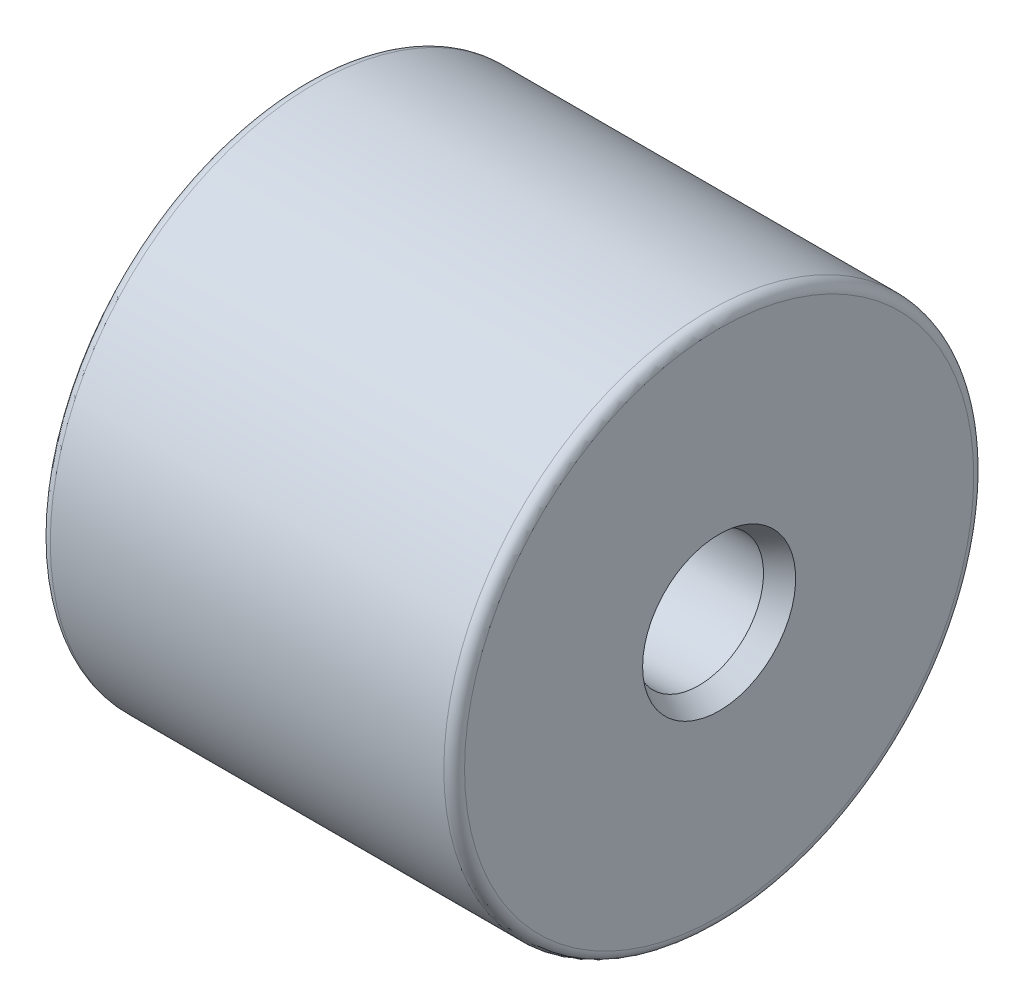
SolidWorks part; units mm, degrees
ref_plane "Front Plane" through (0, 0, 0) normal (0, 0, 1) x (1, 0, 0)
ref_plane "Top Plane" through (0, 0, 0) normal (0, 1, 0) x (1, 0, 0)
ref_plane "Right Plane" through (0, 0, 0) normal (1, 0, 0) x (0, 0, -1)
sketch "Sketch1" plane through (0, 0, 0) normal (0, 0, 1) x (1, 0, 0)
  line L0 (-1000, 0) -> (49000, 0) construction
  line L1 (-15.24, 19.4945) -> (15.24, 19.4945)
  line L2 (15.24, 19.4945) -> (15.24, 4.765)
  line L3 (15.24, 4.765) -> (-15.24, 4.765)
  line L4 (-15.24, 4.765) -> (-15.24, 19.4945)
  line L5 (0, -55) -> (0, 55) construction
  point P5 (0, 19.4945)
  dimension "D1" = 38.989
  dimension "D2" = 9.53
  dimension "D3" = 30.48
revolve "Revolve1" add sketch "Sketch1" angle 360 about L0
chamfer "Chamfer1" distance 1.5 angle 30 1 edges at (-15.24, 0, 4.765)
fillet "Fillet1" radius 0.762 2 edges at (15.24, 0, 19.4945) (-15.24, 0, 19.4945)
chamfer "Chamfer2" distance 1.5 angle 30 1 edges at (15.24, 0, 4.765)
